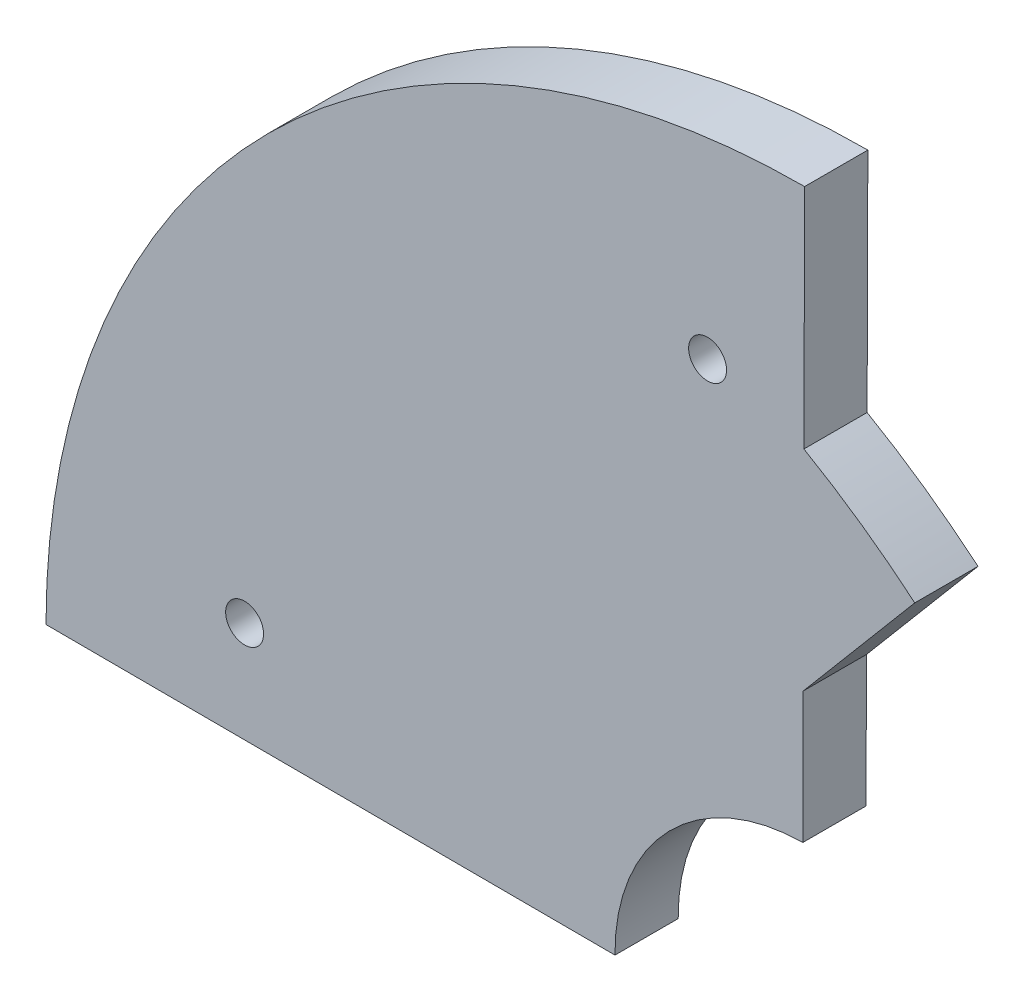
SolidWorks part; units mm, degrees
ref_plane "Front Plane" through (0, 0, 0) normal (0, 0, 1) x (1, 0, 0)
ref_plane "Top Plane" through (0, 0, 0) normal (0, 1, 0) x (1, 0, 0)
ref_plane "Right Plane" through (0, 0, 0) normal (1, 0, 0) x (0, 0, -1)
sketch "Sketch2" plane through (0, 0, 0) normal (0, 0, 1) x (1, 0, 0)
  line L0 (-60, 0) -> (-14.9993, -0.1424)
  line L1 (-0.1424, 14.9993) -> (0, 60)
  circle A0 centre (0, 0) radius 60 construction
  arc A1 (0, 60) -> (-60, 0) centre (0, 0) ccw
  arc A2 (-14.9993, -0.1424) -> (-0.1424, 14.9993) centre (0, 0) cw
  dimension "D1" = 120
  dimension "D2" = 15
extrude "Boss-Extrude1" add sketch "Sketch2" along normal blind 5
sketch "Sketch3" plane through (0, 0, 5) normal (0, 0, 1) x (1, 0, 0)
  line L0 (-0.1424, 14.9993) -> (0, 60) construction
  line L1 (-60, 0) -> (-14.9993, -0.1424) construction
  line L2 (-7.6739, 44.3408) -> (0, 0) construction
  line L3 (0, 0) -> (-44.2914, 7.9543) construction
  arc A0 (-0.0475, 45) -> (-45, -0.0475) centre (0, 0) ccw construction
  arc A1 (0, 60) -> (-60, 0) centre (0, 0) ccw construction
  circle A2 centre (-7.6739, 44.3408) radius 1.5
  circle A3 centre (-44.2914, 7.9543) radius 1.5
  dimension "D1" = 45
  dimension "D2" = 3
  dimension "D3" = 3
  dimension "D4" = 10
  dimension "D5" = 10
extrude "Cut-Extrude1" cut sketch "Sketch3" against normal blind 5
sketch "Sketch4" plane through (0, 0, 5) normal (0, 0, 1) x (1, 0, 0)
  line L0 (-0.1424, 14.9993) -> (0, 60) construction
  line L1 (-30, -10) -> (8.7125, 35.8404) construction
  line L2 (8.7125, 35.8404) -> (-0.1095, 25.3941)
  line L3 (-0.057, 41.9944) -> (-0.1095, 25.3941)
  line L4 (-129.1324, -31.9367) -> (-129.2069, -48.6191)
  line L5 (-120.3244, -38.1289) -> (-129.2069, -48.6191)
  arc A0 (-0.057, 41.9944) -> (8.7125, 35.8404) centre (-30, -10) cw
  arc A1 (-129.1324, -31.9367) -> (-120.3244, -38.1289) centre (-159.0966, -83.9188) cw
  point P0 (-30, -10)
  dimension "D3" = 60
  dimension "D1" = 30
  dimension "D2" = 10
  dimension "D4" = 40
extrude "Boss-Extrude2" add sketch "Sketch4" against normal blind 5 contours A0 L2 L3
